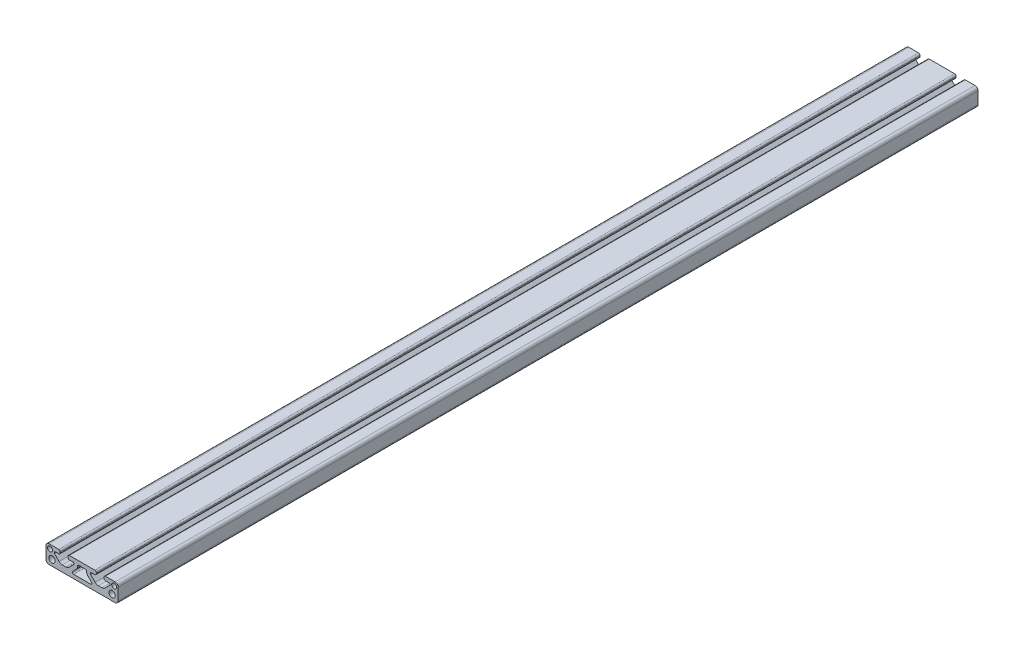
SolidWorks part; units mm, degrees
material "6105-T5 Aluminum"
ref_plane "Front Plane" through (0, 0, 0) normal (0, 0, 1) x (1, 0, 0)
ref_plane "Top Plane" through (0, 0, 0) normal (0, 1, 0) x (1, 0, 0)
ref_plane "Right Plane" through (0, 0, 0) normal (1, 0, 0) x (0, 0, -1)
sketch "Sketch1" plane through (0, 0, 0) normal (0, 0, 1) x (1, 0, 0)
  line L0 (-9.9443, 6.232) -> (-6.0902, 10.0861)
  line L1 (-4.699, 13.4447) -> (-4.699, 13.716)
  line L2 (-3.429, 14.986) -> (3.429, 14.986)
  line L3 (4.699, 13.716) -> (4.699, 13.4447)
  line L4 (6.0902, 10.0861) -> (9.9443, 6.232)
  line L5 (9.0463, 4.064) -> (-9.0463, 4.064)
  line L6 (23.114, 17.4752) -> (23.114, 16.5608)
  line L7 (24.6888, 14.986) -> (28.448, 14.986)
  line L8 (29.337, 14.097) -> (29.337, 13.5289)
  line L9 (29.0766, 12.9003) -> (24.3055, 8.1292)
  line L10 (20.9469, 6.738) -> (17.1531, 6.738)
  line L11 (13.7945, 8.1292) -> (9.0234, 12.9003)
  line L12 (8.763, 13.5289) -> (8.763, 14.097)
  line L13 (9.652, 14.986) -> (13.4112, 14.986)
  line L14 (14.986, 16.5608) -> (14.986, 17.4752)
  line L15 (13.4112, 19.05) -> (-13.4112, 19.05)
  line L16 (-14.986, 17.4752) -> (-14.986, 16.5608)
  line L17 (-13.4112, 14.986) -> (-9.652, 14.986)
  line L18 (-8.763, 14.097) -> (-8.763, 13.5289)
  line L19 (-9.0234, 12.9003) -> (-13.7945, 8.1292)
  line L20 (-17.1531, 6.738) -> (-20.9469, 6.738)
  line L21 (-24.3055, 8.1292) -> (-29.0766, 12.9003)
  line L22 (-29.337, 13.5289) -> (-29.337, 14.097)
  line L23 (-28.448, 14.986) -> (-24.6888, 14.986)
  line L24 (-23.114, 16.5608) -> (-23.114, 17.4752)
  line L25 (-24.6888, 19.05) -> (-34.925, 19.05)
  line L26 (-38.1, 15.875) -> (-38.1, 3.175)
  line L27 (-34.925, 0) -> (34.925, 0)
  line L28 (38.1, 3.175) -> (38.1, 15.875)
  line L29 (34.925, 19.05) -> (24.6888, 19.05)
  circle A0 centre (-33.909, 14.8082) radius 2.6035
  circle A1 centre (31.75, 6.35) radius 3.3274
  circle A2 centre (33.909, 14.8082) radius 2.6035
  circle A3 centre (-31.75, 6.35) radius 3.3274
  arc A4 (-6.0902, 10.0861) -> (-4.699, 13.4447) centre (-9.4488, 13.4447) ccw
  arc A5 (-3.429, 14.986) -> (-4.699, 13.716) centre (-3.429, 13.716) ccw
  arc A6 (4.699, 13.716) -> (3.429, 14.986) centre (3.429, 13.716) ccw
  arc A7 (4.699, 13.4447) -> (6.0902, 10.0861) centre (9.4488, 13.4447) ccw
  arc A8 (9.0463, 4.064) -> (9.9443, 6.232) centre (9.0463, 5.334) ccw
  arc A9 (-9.9443, 6.232) -> (-9.0463, 4.064) centre (-9.0463, 5.334) ccw
  arc A10 (24.6888, 19.05) -> (23.114, 17.4752) centre (24.6888, 17.4752) ccw
  arc A11 (23.114, 16.5608) -> (24.6888, 14.986) centre (24.6888, 16.5608) ccw
  arc A12 (29.337, 14.097) -> (28.448, 14.986) centre (28.448, 14.097) ccw
  arc A13 (29.0766, 12.9003) -> (29.337, 13.5289) centre (28.448, 13.5289) ccw
  arc A14 (20.9469, 6.738) -> (24.3055, 8.1292) centre (20.9469, 11.4878) ccw
  arc A15 (13.7945, 8.1292) -> (17.1531, 6.738) centre (17.1531, 11.4878) ccw
  arc A16 (8.763, 13.5289) -> (9.0234, 12.9003) centre (9.652, 13.5289) ccw
  arc A17 (9.652, 14.986) -> (8.763, 14.097) centre (9.652, 14.097) ccw
  arc A18 (13.4112, 14.986) -> (14.986, 16.5608) centre (13.4112, 16.5608) ccw
  arc A19 (14.986, 17.4752) -> (13.4112, 19.05) centre (13.4112, 17.4752) ccw
  arc A20 (-13.4112, 19.05) -> (-14.986, 17.4752) centre (-13.4112, 17.4752) ccw
  arc A21 (-14.986, 16.5608) -> (-13.4112, 14.986) centre (-13.4112, 16.5608) ccw
  arc A22 (-8.763, 14.097) -> (-9.652, 14.986) centre (-9.652, 14.097) ccw
  arc A23 (-9.0234, 12.9003) -> (-8.763, 13.5289) centre (-9.652, 13.5289) ccw
  arc A24 (-17.1531, 6.738) -> (-13.7945, 8.1292) centre (-17.1531, 11.4878) ccw
  arc A25 (-24.3055, 8.1292) -> (-20.9469, 6.738) centre (-20.9469, 11.4878) ccw
  arc A26 (-29.337, 13.5289) -> (-29.0766, 12.9003) centre (-28.448, 13.5289) ccw
  arc A27 (-28.448, 14.986) -> (-29.337, 14.097) centre (-28.448, 14.097) ccw
  arc A28 (-24.6888, 14.986) -> (-23.114, 16.5608) centre (-24.6888, 16.5608) ccw
  arc A29 (-23.114, 17.4752) -> (-24.6888, 19.05) centre (-24.6888, 17.4752) ccw
  arc A30 (-34.925, 19.05) -> (-38.1, 15.875) centre (-34.925, 15.875) ccw
  arc A31 (-38.1, 3.175) -> (-34.925, 0) centre (-34.925, 3.175) ccw
  arc A32 (34.925, 0) -> (38.1, 3.175) centre (34.925, 3.175) ccw
  arc A33 (38.1, 15.875) -> (34.925, 19.05) centre (34.925, 15.875) ccw
extrude "Extrude1" add sketch "Sketch1" against normal blind 908.05
